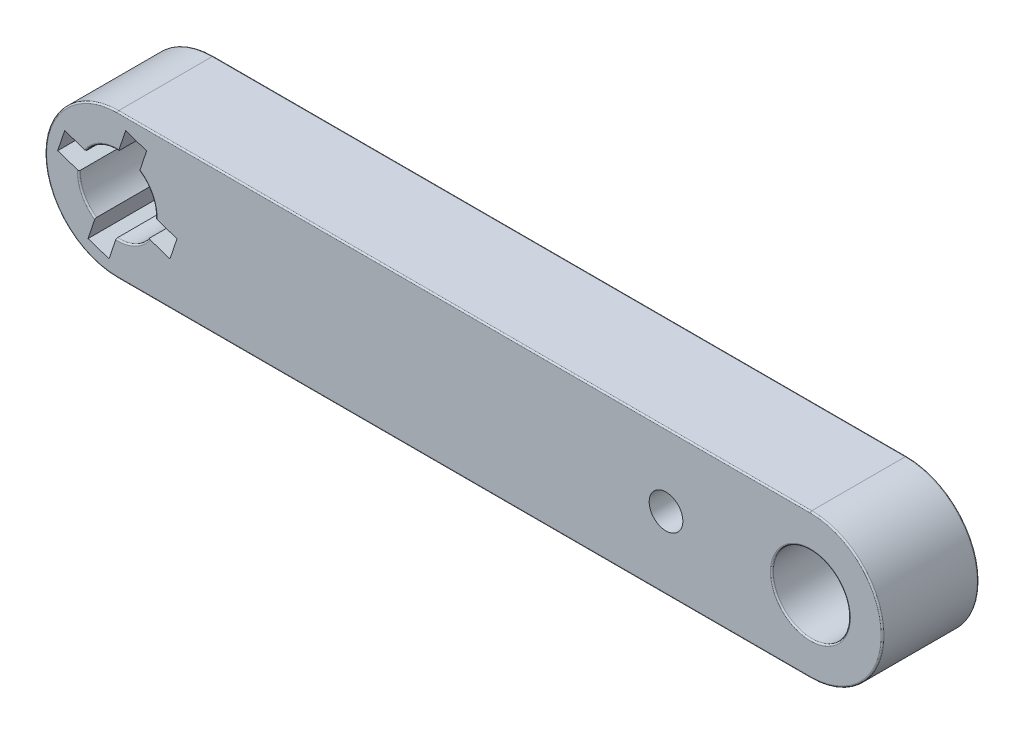
SolidWorks part; units mm, degrees
ref_plane "Front Plane" through (0, 0, 0) normal (0, 0, 1) x (1, 0, 0)
ref_plane "Top Plane" through (0, 0, 0) normal (0, 1, 0) x (1, 0, 0)
ref_plane "Right Plane" through (0, 0, 0) normal (1, 0, 0) x (0, 0, -1)
sketch "Sketch1" plane through (0, 0, 0) normal (0, 0, 1) x (1, 0, 0)
  line L1 (-36, 7.5) -> (36, 7.5) construction
  line L2 (-36, 7.5) -> (-36, -7.5) construction
  line L3 (-36, -7.5) -> (36, -7.5) construction
  line L4 (36, 7.5) -> (36, -7.5) construction
  line L5 (-36, 7.5) -> (36, -7.5) construction
  line L6 (-36, -7.5) -> (36, 7.5) construction
  line L7 (-36, 7.5) -> (36, 7.5)
  line L9 (-36, -7.5) -> (36, -7.5)
  line L11 (-36, 7.5) -> (36, -7.5) construction
  line L12 (-36, -7.5) -> (36, 7.5) construction
  arc A0 (-36, 7.5) -> (-36, -7.5) centre (-36, 0) ccw
  arc A1 (36, -7.5) -> (36, 7.5) centre (36, 0) ccw
  circle A2 centre (-36, 0) radius 4
  circle A3 centre (36, 0) radius 4
  point P0 (0, 0)
  point P12 (0, 0)
  dimension "D3" = 8
  dimension "D1" = 72
  dimension "D2" = 15
  dimension "D4" = 15
extrude "Boss-Extrude1" add sketch "Sketch1" along normal mid plane 10
fillet "Fillet2" radius 0.15 12 edges at (40, 0, -5) (-32, 0, -5) (0, 7.5, -5) (-43.5, 0, -5) (0, -7.5, -5) (43.5, 0, -5) (40, 0, 5) (-43.5, 0, 5) (0, 7.5, 5) (43.5, 0, 5) (0, -7.5, 5) (-32, 0, 5)
sketch "Sketch2" plane through (0, 0, -5) normal (0, 0, -1) x (-1, 0, 0)
  line L0 (-36, 7.5) -> (36, 7.5) construction
  line L1 (-26, 4) -> (-16, 4)
  line L2 (-26, 4) -> (-26, -3.9994)
  line L3 (-26, -3.9994) -> (-16, -3.9994)
  line L4 (-16, 4) -> (-16, -3.9994)
  line L5 (36, -7.5) -> (-36, -7.5) construction
  circle A0 centre (-36, 0) radius 4.15 construction
  dimension "D3" = 10
  dimension "D1" = 3.5
  dimension "D2" = 3.5006
  dimension "D4" = 20
extrude "Cut-Extrude1" cut sketch "Sketch2" against normal blind 3
sketch "Sketch3" plane through (0, 0, -2) normal (0, 0, -1) x (-1, 0, 0)
  line L0 (-26, 4) -> (-16, -3.9994) construction
  line L1 (-26, -3.9994) -> (-16, 4) construction
  circle A0 centre (-21, 0.0003) radius 1.75
  dimension "D1" = 3.5
extrude "Cut-Extrude2" cut sketch "Sketch3" against normal through all
sketch "Sketch5" plane through (0, 0, 5) normal (0, 0, 1) x (1, 0, 0)
  line L0 (-29.8031, -0.8619) -> (-32.002, -0.1257)
  line L1 (-33.6932, 3.2678) -> (-32.9571, 5.4668)
  line L2 (-32.9571, 5.4668) -> (-35.1381, 6.1969)
  line L3 (-35.1381, 6.1969) -> (-35.8743, 3.998)
  line L4 (-39.2678, 2.3068) -> (-41.4668, 3.0429)
  line L5 (-41.4668, 3.0429) -> (-42.1969, 0.8619)
  line L6 (-42.1969, 0.8619) -> (-39.998, 0.1257)
  line L7 (-38.3068, -3.2678) -> (-39.0429, -5.4668)
  line L8 (-39.0429, -5.4668) -> (-36.8619, -6.1969)
  line L9 (-36.8619, -6.1969) -> (-36.1257, -3.998)
  line L10 (-32.7322, -2.3068) -> (-30.5332, -3.0429)
  line L11 (-30.5332, -3.0429) -> (-29.8031, -0.8619)
  line L12 (-29.9929, -0.9565) -> (-32.157, -0.232)
  line L13 (-33.8714, 3.2081) -> (-33.1469, 5.3721)
  line L14 (-33.1469, 5.3721) -> (-35.0435, 6.0071)
  line L15 (-35.0435, 6.0071) -> (-35.768, 3.843)
  line L16 (-39.2081, 2.1286) -> (-41.3721, 2.8531)
  line L17 (-41.3721, 2.8531) -> (-42.0071, 0.9565)
  line L18 (-42.0071, 0.9565) -> (-39.843, 0.232)
  line L19 (-38.1286, -3.2081) -> (-38.8531, -5.3721)
  line L20 (-38.8531, -5.3721) -> (-36.9565, -6.0071)
  line L21 (-36.9565, -6.0071) -> (-36.232, -3.843)
  line L22 (-32.7919, -2.1286) -> (-30.6279, -2.8531)
  line L23 (-30.6279, -2.8531) -> (-29.9929, -0.9565)
  line L24 (-29.9929, -0.9565) -> (-32.157, -0.232) construction
  line L25 (-33.8714, 3.2081) -> (-33.1469, 5.3721) construction
  line L26 (-33.1469, 5.3721) -> (-35.0435, 6.0071) construction
  line L27 (-35.0435, 6.0071) -> (-35.768, 3.843) construction
  line L28 (-39.2081, 2.1286) -> (-41.3721, 2.8531) construction
  line L29 (-41.3721, 2.8531) -> (-42.0071, 0.9565) construction
  line L30 (-42.0071, 0.9565) -> (-39.843, 0.232) construction
  line L31 (-38.1286, -3.2081) -> (-38.8531, -5.3721) construction
  line L32 (-38.8531, -5.3721) -> (-36.9565, -6.0071) construction
  line L33 (-36.9565, -6.0071) -> (-36.232, -3.843) construction
  line L34 (-32.7919, -2.1286) -> (-30.6279, -2.8531) construction
  line L35 (-30.6279, -2.8531) -> (-29.9929, -0.9565) construction
  arc A0 (-32.002, -0.1257) -> (-33.6932, 3.2678) centre (-36, 0) ccw
  arc A1 (-35.8743, 3.998) -> (-39.2678, 2.3068) centre (-36, 0) ccw
  arc A2 (-39.998, 0.1257) -> (-38.3068, -3.2678) centre (-36, 0) ccw
  arc A3 (-36.1257, -3.998) -> (-32.7322, -2.3068) centre (-36, 0) ccw
  arc A4 (-32.157, -0.232) -> (-33.8714, 3.2081) centre (-36, 0) ccw
  arc A5 (-35.768, 3.843) -> (-39.2081, 2.1286) centre (-36, 0) ccw
  arc A6 (-39.843, 0.232) -> (-38.1286, -3.2081) centre (-36, 0) ccw
  arc A7 (-36.232, -3.843) -> (-32.7919, -2.1286) centre (-36, 0) ccw
  arc A8 (-32.157, -0.232) -> (-33.8714, 3.2081) centre (-36, 0) ccw construction
  arc A9 (-35.768, 3.843) -> (-39.2081, 2.1286) centre (-36, 0) ccw construction
  arc A10 (-39.843, 0.232) -> (-38.1286, -3.2081) centre (-36, 0) ccw construction
  arc A11 (-36.232, -3.843) -> (-32.7919, -2.1286) centre (-36, 0) ccw construction
  dimension "D1" = 0
  dimension "D2" = 0.15
extrude "Cut-Extrude3" cut sketch "Sketch5" against normal through all
